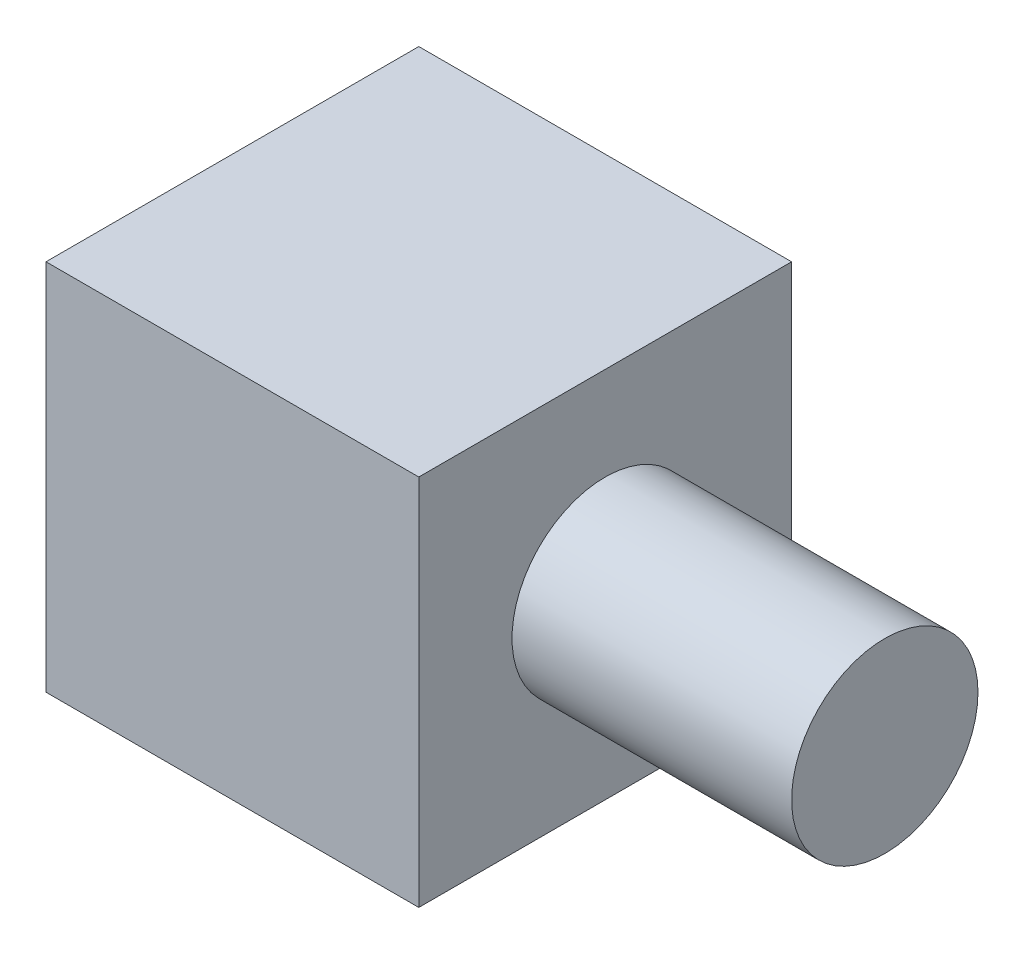
SolidWorks part; units mm, degrees
material "2024 Сплав"
ref_plane "Спереди" through (0, 0, 0) normal (0, 0, 1) x (1, 0, 0)
ref_plane "Сверху" through (0, 0, 0) normal (0, 1, 0) x (1, 0, 0)
ref_plane "Справа" through (0, 0, 0) normal (1, 0, 0) x (0, 0, -1)
other "Центр тяжести"
other "Configuration Table"
sketch "Эскиз1" plane through (0, 0, 0) normal (0, 0, 1) x (1, 0, 0)
  line L1 (-50, -50) -> (50, -50)
  line L2 (-50, -50) -> (-50, 50)
  line L3 (-50, 50) -> (50, 50)
  line L4 (50, -50) -> (50, 50)
  line L5 (-50, -50) -> (50, 50) construction
  line L6 (-50, 50) -> (50, -50) construction
  point P0 (0, 0)
  dimension "D1" = 100
  dimension "D2" = 100
extrude "Бобышка-Вытянуть1" add sketch "Эскиз1" along normal blind 100
sketch "Эскиз2" plane through (50, 0, 0) normal (1, 0, 0) x (0, 0, -1)
  circle A0 centre (-50, 0) radius 25
  point P2 (-49.0933, 0)
extrude "Бобышка-Вытянуть2" add sketch "Эскиз2" along normal blind 75
ref_point "Точка2"
